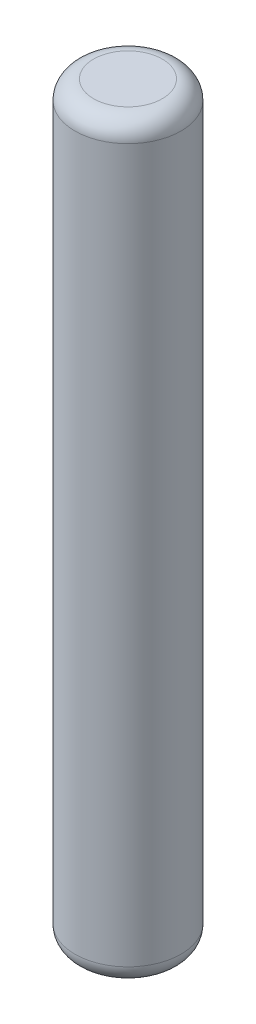
SolidWorks part; units mm, degrees
ref_plane "Front Plane" through (0, 0, 0) normal (0, 0, 1) x (1, 0, 0)
ref_plane "Top Plane" through (0, 0, 0) normal (0, 1, 0) x (1, 0, 0)
ref_plane "Right Plane" through (0, 0, 0) normal (1, 0, 0) x (0, 0, -1)
sketch "Sketch1" plane through (0, 0, 0) normal (0, 1, 0) x (1, 0, 0)
  circle A0 centre (0, 0) radius 2.84
extrude "Boss-Extrude1" add sketch "Sketch1" along normal blind 40.18
fillet "Fillet1" radius 1 1 edges at (0, 40.18, 2.84)
fillet "Fillet2" radius 1 1 edges at (0, 0, 2.84)
